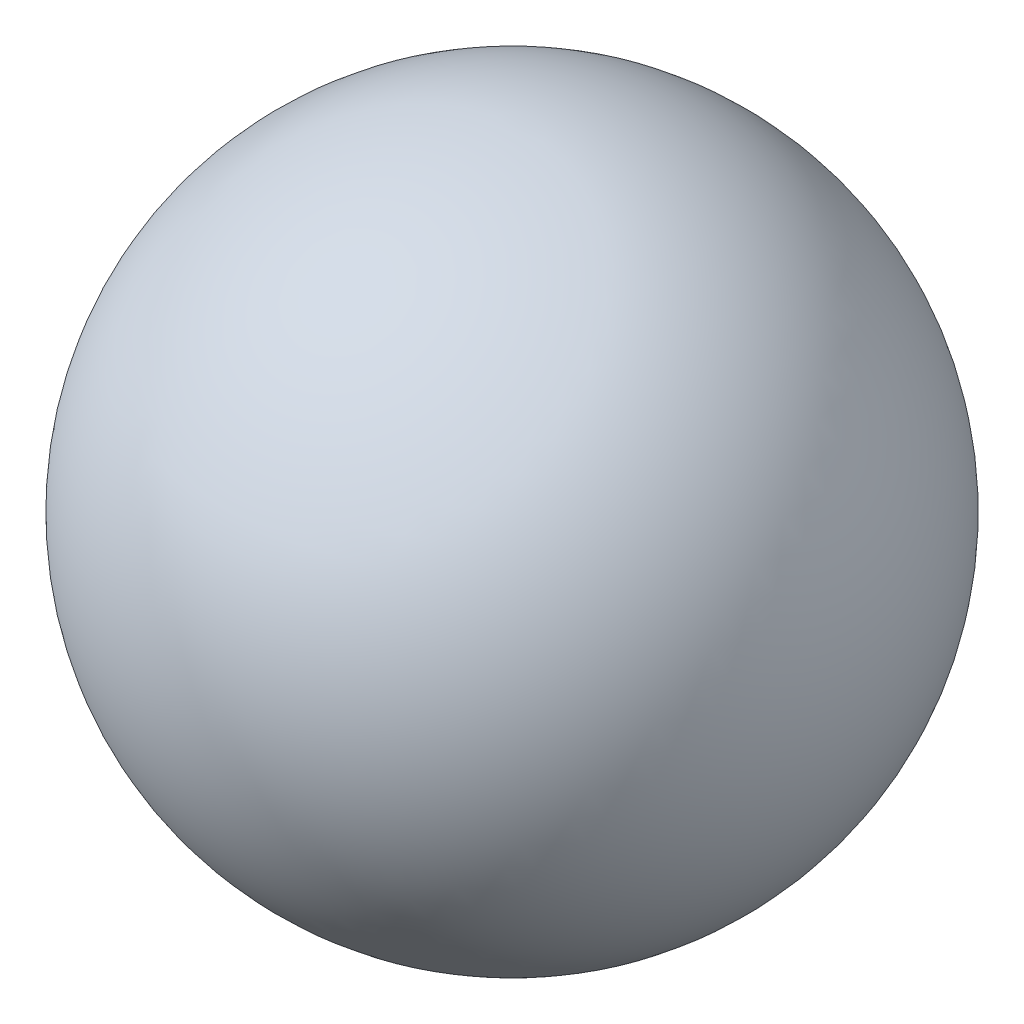
SolidWorks part; units mm, degrees
ref_plane "Front" through (0, 0, 0) normal (0, 0, 1) x (1, 0, 0)
ref_plane "Top" through (0, 0, 0) normal (0, 1, 0) x (1, 0, 0)
ref_plane "Right" through (0, 0, 0) normal (1, 0, 0) x (0, 0, -1)
other "Configuration Table"
sketch "Sketch1" plane through (0, 0, 0) normal (0, 0, 1) x (1, 0, 0)
  line L0 (0, 116.8447) -> (0, -120.4399) construction
  line L1 (0, 400) -> (0, 300)
  line L2 (0, -300) -> (0, -400)
  arc A0 (0, 300) -> (0, -300) centre (0, 0) cw
  arc A1 (0, 400) -> (0, -400) centre (0, 0) cw
  dimension "D1" = 300
  dimension "D2" = 400
revolve "Revolve1" add sketch "Sketch1" angle 360 about L0
